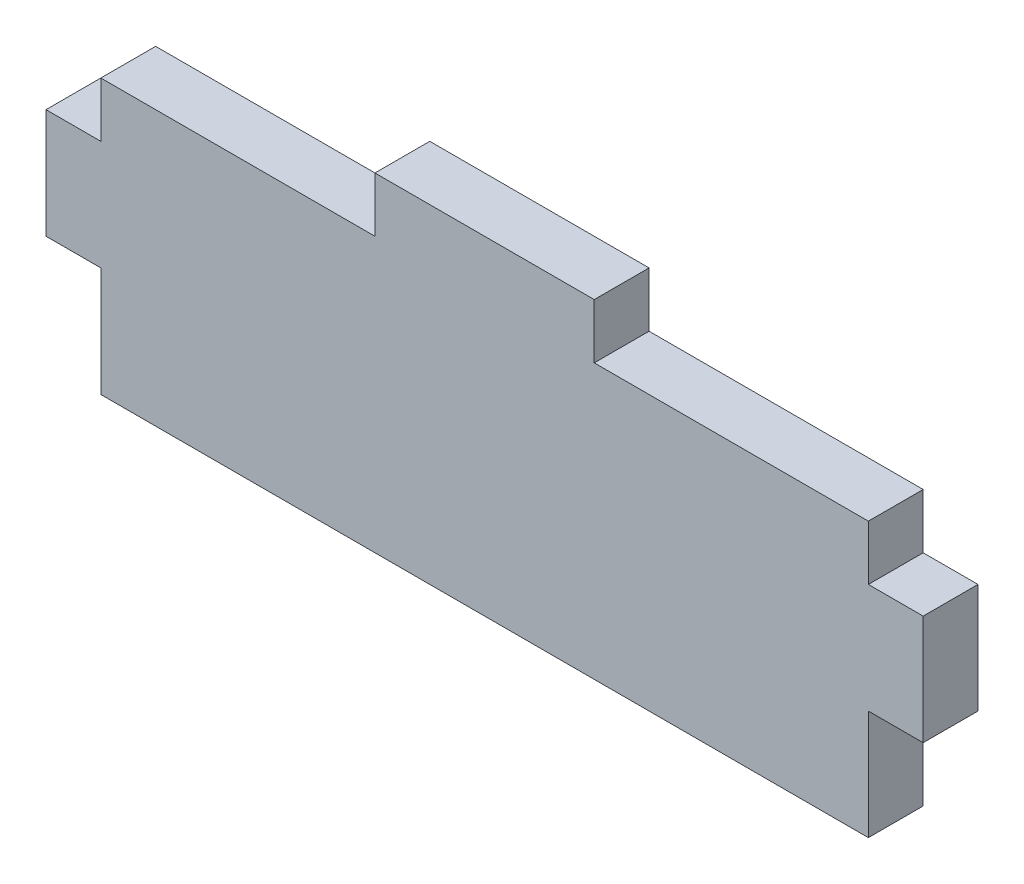
SolidWorks part; units mm, degrees
ref_plane "Front Plane" through (0, 0, 0) normal (0, 0, 1) x (1, 0, 0)
ref_plane "Top Plane" through (0, 0, 0) normal (0, 1, 0) x (1, 0, 0)
ref_plane "Right Plane" through (0, 0, 0) normal (1, 0, 0) x (0, 0, -1)
sketch "Sketch1" plane through (0, 0, 0) normal (0, 0, 1) x (1, 0, 0)
  line L0 (90.1337, 9.319) -> (90.1337, 49.648) construction
  line L1 (-5.1163, 19.0519) -> (83.7837, 19.0519)
  line L2 (-5.1163, 19.0519) -> (-5.1163, -12.6981)
  line L3 (-5.1163, -12.6981) -> (83.7837, -12.6981)
  line L4 (83.7837, 19.0519) -> (83.7837, -12.6981)
  line L5 (-11.4663, 12.7019) -> (-5.1163, 12.7019)
  line L6 (-11.4663, 12.7019) -> (-11.4663, 0.0019)
  line L7 (-11.4663, 0.0019) -> (-5.1163, 0.0019)
  line L8 (-5.1163, 12.7019) -> (-5.1163, 0.0019)
  line L9 (83.7837, 12.7019) -> (90.1337, 12.7019)
  line L10 (83.7837, 12.7019) -> (83.7837, 0.0019)
  line L11 (83.7837, 0.0019) -> (90.1337, 0.0019)
  line L12 (90.1337, 12.7019) -> (90.1337, 0.0019)
  line L13 (26.6337, 25.4019) -> (52.0337, 25.4019)
  line L14 (26.6337, 25.4019) -> (26.6337, 19.0519)
  line L15 (26.6337, 19.0519) -> (52.0337, 19.0519)
  line L16 (52.0337, 25.4019) -> (52.0337, 19.0519)
  dimension "D1" = 88.9
  dimension "D2" = 31.75
  dimension "D3" = 12.7
  dimension "D5" = 6.35
  dimension "D6" = 6.35
  dimension "D7" = 12.7
  dimension "D9" = 6.35
  dimension "D10" = 25.4
  dimension "D11" = 31.75
  dimension "D4" = 6.35
  dimension "D8" = 6.35
extrude "Boss-Extrude1" add sketch "Sketch1" along normal blind 6.35 contours L4 L1 L2 L3 | L16 L13 L14 L1 | L12 L9 L4 L11 | L6 L7 L2 L5
equation "\"width\"= 3.5in"
equation "\"Height\"= 18in"
equation "\"thick\"= 0.25"
equation "\"D1@Sketch1\"=\"width\""
equation "\"D2@Sketch1\"=1.5-\"thick\""
equation "\"D5@Sketch1\"=\"thick\""
equation "\"D6@Sketch1\"=\"thick\""
equation "\"D7@Sketch1\"=0.5"
equation "\"D9@Sketch1\"=\"thick\""
equation "\"D1@Boss-Extrude1\"=\"thick\""
equation "\"D4@Sketch1\"=0.5-\"thick\""
equation "\"D8@Sketch1\"=0.5-\"thick\""
